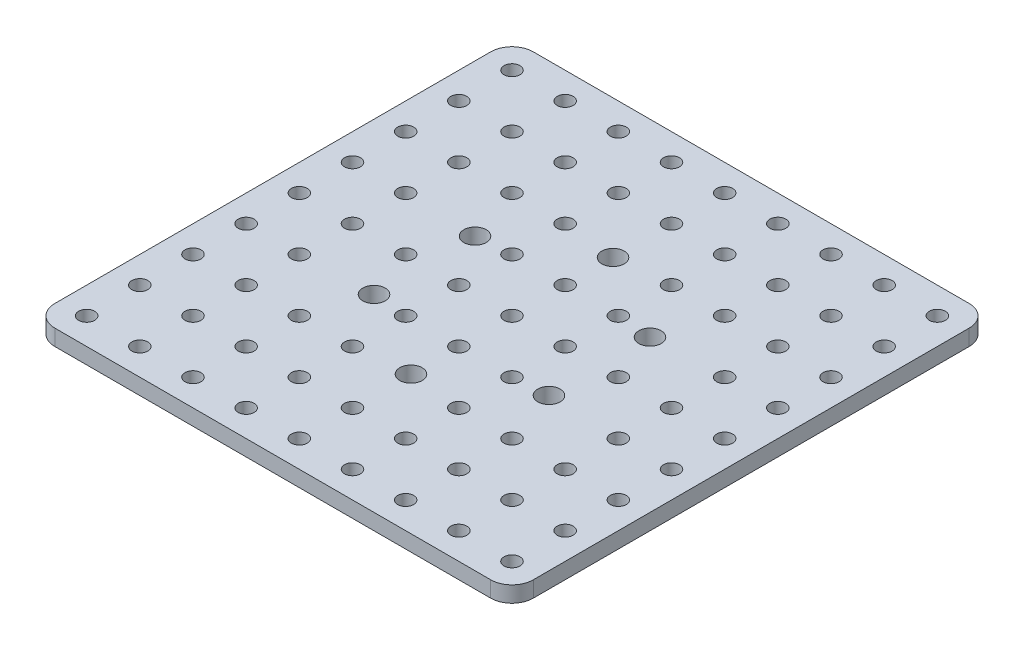
SolidWorks part; units mm, degrees
material "Thornel Mat VMA"
ref_plane "前视基准面" through (0, 0, 0) normal (0, 0, 1) x (1, 0, 0)
ref_plane "上视基准面" through (0, 0, 0) normal (0, 1, 0) x (1, 0, 0)
ref_plane "右视基准面" through (0, 0, 0) normal (1, 0, 0) x (0, 0, -1)
other "Configuration Table"
sketch "草图1" plane through (0, 0, 0) normal (0, 1, 0) x (1, 0, 0)
  line L1 (-45, -45) -> (45, -45)
  line L2 (-45, -45) -> (-45, 45)
  line L3 (-45, 45) -> (45, 45)
  line L4 (45, -45) -> (45, 45)
  line L5 (0, 45) -> (0, -45) construction
  line L6 (-45, 0) -> (45, 0) construction
  point P0 (0, 0)
  dimension "D1" = 90
  dimension "D2" = 90
extrude "凸台-拉伸1" add sketch "草图1" along normal blind 3
sketch "草图2" plane through (0, 3, 0) normal (0, 1, 0) x (1, 0, 0)
  circle A0 centre (-40, 40) radius 1.5
  circle A1 centre (40, 40) radius 1.5
  circle A2 centre (40, -40) radius 1.5
  circle A3 centre (-40, -40) radius 1.5
  point P12 (0, 0)
  dimension "D1" = 40
  dimension "D2" = 40
  dimension "D3" = 3
  dimension "D4" = 4
extrude "切除-拉伸1" cut sketch "草图2" against normal through all
sketch "草图3" plane through (0, 3, 0) normal (0, 1, 0) x (1, 0, 0)
  circle A1 centre (0, 0) radius 1.5
  circle A2 centre (10, 0) radius 1.5
  circle A3 centre (20, 0) radius 1.5
  circle A4 centre (30, 0) radius 1.5
  circle A5 centre (40, 0) radius 1.5
  circle A6 centre (10, 10) radius 1.5
  circle A8 centre (30, 10) radius 1.5
  circle A9 centre (40, 10) radius 1.5
  circle A10 centre (10, 20) radius 1.5
  circle A11 centre (20, 20) radius 1.5
  circle A12 centre (30, 20) radius 1.5
  circle A13 centre (40, 20) radius 1.5
  circle A14 centre (10, 30) radius 1.5
  circle A15 centre (20, 30) radius 1.5
  circle A16 centre (30, 30) radius 1.5
  circle A17 centre (40, 30) radius 1.5
  circle A18 centre (10, 40) radius 1.5
  circle A19 centre (20, 40) radius 1.5
  circle A20 centre (30, 40) radius 1.5
  circle A21 centre (40, 40) radius 1.5
  circle A22 centre (0, 10) radius 1.5
  circle A24 centre (0, 30) radius 1.5
  circle A25 centre (0, 40) radius 1.5
  circle A26 centre (-10, 0) radius 1.5
  circle A27 centre (-20, 0) radius 1.5
  circle A28 centre (-30, 0) radius 1.5
  circle A29 centre (-40, 0) radius 1.5
  circle A30 centre (-10, -10) radius 1.5
  circle A32 centre (-30, -10) radius 1.5
  circle A33 centre (-40, -10) radius 1.5
  circle A34 centre (-10, -20) radius 1.5
  circle A35 centre (-20, -20) radius 1.5
  circle A36 centre (-30, -20) radius 1.5
  circle A37 centre (-40, -20) radius 1.5
  circle A38 centre (-10, -30) radius 1.5
  circle A39 centre (-20, -30) radius 1.5
  circle A40 centre (-30, -30) radius 1.5
  circle A41 centre (-40, -30) radius 1.5
  circle A42 centre (-10, -40) radius 1.5
  circle A43 centre (-20, -40) radius 1.5
  circle A44 centre (-30, -40) radius 1.5
  circle A45 centre (-40, -40) radius 1.5
  circle A46 centre (0, -10) radius 1.5
  circle A48 centre (0, -30) radius 1.5
  circle A49 centre (0, -40) radius 1.5
  circle A50 centre (0, 20) radius 1.5 [skipped]
  circle A51 centre (-20, -10) radius 1.5 [skipped]
  circle A52 centre (20, 10) radius 1.5 [skipped]
  circle A53 centre (0, -20) radius 1.5 [skipped]
  dimension "D1" = 3
  dimension "D2" = 5
  dimension "D3" = 5
  dimension "D4" = 5
  dimension "D5" = 5
extrude "切除-拉伸2" cut sketch "草图3" against normal through all
sketch "草图5" plane through (0, 3, 0) normal (0, 1, 0) x (1, 0, 0)
  circle A0 centre (0, 0) radius 1.5
  circle A1 centre (-10, 0) radius 1.5
  circle A2 centre (-20, 0) radius 1.5
  circle A3 centre (-30, 0) radius 1.5
  circle A4 centre (-40, 0) radius 1.5
  circle A5 centre (-10, 10) radius 1.5
  circle A7 centre (-30, 10) radius 1.5
  circle A8 centre (-40, 10) radius 1.5
  circle A9 centre (-10, 20) radius 1.5
  circle A10 centre (-20, 20) radius 1.5
  circle A11 centre (-30, 20) radius 1.5
  circle A12 centre (-40, 20) radius 1.5
  circle A13 centre (-10, 30) radius 1.5
  circle A14 centre (-20, 30) radius 1.5
  circle A15 centre (-30, 30) radius 1.5
  circle A16 centre (-40, 30) radius 1.5
  circle A17 centre (-10, 40) radius 1.5
  circle A18 centre (-20, 40) radius 1.5
  circle A19 centre (-30, 40) radius 1.5
  circle A20 centre (-40, 40) radius 1.5
  circle A21 centre (0, 10) radius 1.5
  circle A23 centre (0, 30) radius 1.5
  circle A24 centre (0, 40) radius 1.5
  circle A25 centre (10, 0) radius 1.5
  circle A26 centre (20, 0) radius 1.5
  circle A27 centre (30, 0) radius 1.5
  circle A28 centre (40, 0) radius 1.5
  circle A29 centre (10, -10) radius 1.5
  circle A31 centre (30, -10) radius 1.5
  circle A32 centre (40, -10) radius 1.5
  circle A33 centre (10, -20) radius 1.5
  circle A34 centre (20, -20) radius 1.5
  circle A35 centre (30, -20) radius 1.5
  circle A36 centre (40, -20) radius 1.5
  circle A37 centre (10, -30) radius 1.5
  circle A38 centre (20, -30) radius 1.5
  circle A39 centre (30, -30) radius 1.5
  circle A40 centre (40, -30) radius 1.5
  circle A41 centre (10, -40) radius 1.5
  circle A42 centre (20, -40) radius 1.5
  circle A43 centre (30, -40) radius 1.5
  circle A44 centre (40, -40) radius 1.5
  circle A45 centre (0, -10) radius 1.5
  circle A47 centre (0, -30) radius 1.5
  circle A48 centre (0, -40) radius 1.5
  circle A49 centre (-20, 10) radius 1.5 [skipped]
  circle A50 centre (20, -10) radius 1.5 [skipped]
  circle A51 centre (0, 20) radius 1.5 [skipped]
  circle A52 centre (0, -20) radius 1.5 [skipped]
  dimension "D1" = 5
  dimension "D2" = 5
  dimension "D3" = 5
  dimension "D4" = 5
extrude "切除-拉伸3" cut sketch "草图5" against normal through all
fillet "圆角1" radius 4 4 edges at (-45, 1.5, 45) (45, 1.5, 45) (45, 1.5, -45) (-45, 1.5, -45)
sketch "草图6" plane through (0, 3, 0) normal (0, 1, 0) x (1, 0, 0)
  circle A0 centre (0, 19) radius 2.1
  circle A1 centre (16.4545, 9.5) radius 2.1
  circle A2 centre (16.4545, -9.5) radius 2.1
  circle A3 centre (0, -19) radius 2.1
  circle A4 centre (-16.4545, -9.5) radius 2.1
  circle A5 centre (-16.4545, 9.5) radius 2.1
  point P15 (0, 0)
  dimension "D1" = 19
  dimension "D2" = 0
  dimension "D3" = 4.2
  dimension "D4" = 6
extrude "切除-拉伸5" cut sketch "草图6" against normal through all
